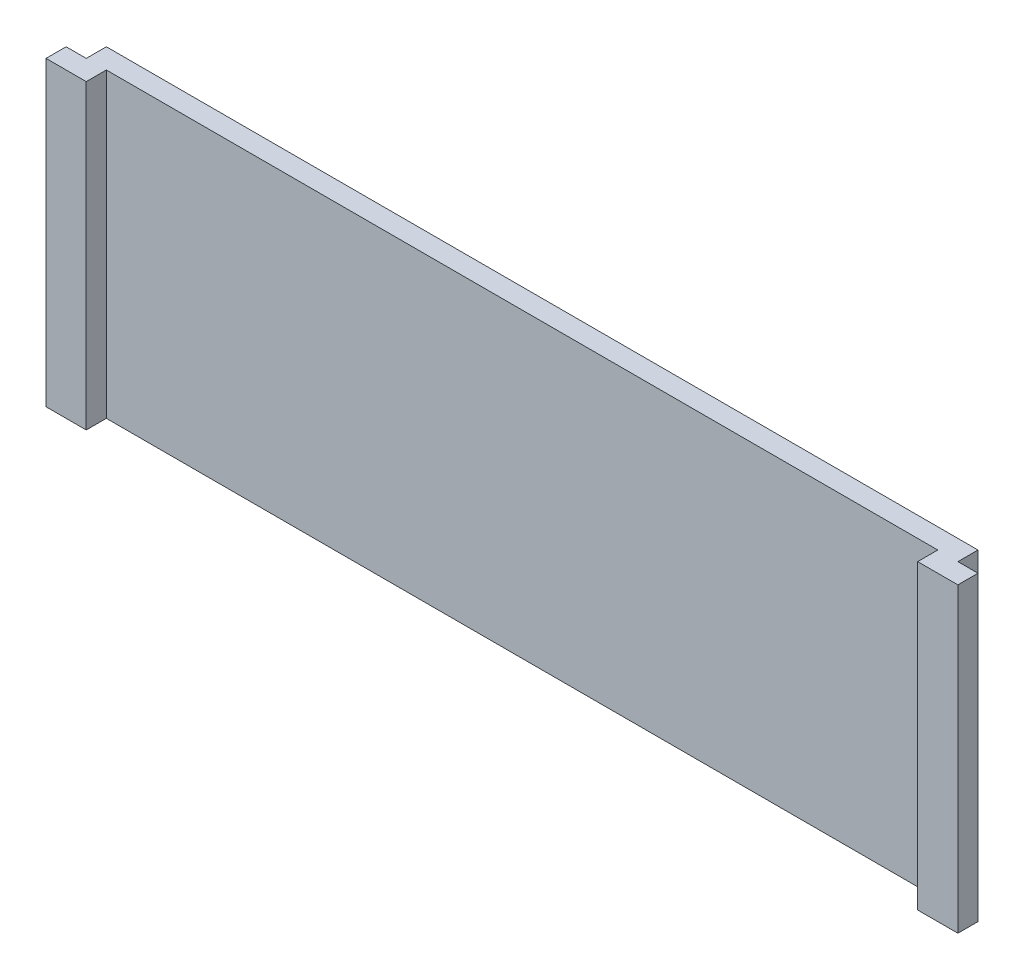
SolidWorks part; units mm, degrees
material "ABS"
ref_plane "前基準面" through (0, 0, 0) normal (0, 0, 1) x (1, 0, 0)
ref_plane "上基準面" through (0, 0, 0) normal (0, 1, 0) x (1, 0, 0)
ref_plane "右基準面" through (0, 0, 0) normal (1, 0, 0) x (0, 0, -1)
sketch "草圖1" plane through (0, 0, 0) normal (0, 0, 1) x (1, 0, 0)
  line L1 (-13.7647, 33.7349) -> (116.2353, 33.7349)
  line L2 (-13.7647, 33.7349) -> (-13.7647, -11.2651)
  line L3 (-13.7647, -11.2651) -> (116.2353, -11.2651)
  line L4 (116.2353, 33.7349) -> (116.2353, -11.2651)
  dimension "D1" = 130
  dimension "D2" = 45
extrude "填料-伸長1" add sketch "草圖1" along normal blind 3
sketch "草圖2" plane through (0, 0, 3) normal (0, 0, 1) x (1, 0, 0)
  line L0 (-13.7647, -11.2651) -> (116.2353, -11.2651) construction
  line L1 (-13.7647, 33.7349) -> (-10.7647, 33.7349)
  line L2 (-13.7647, 33.7349) -> (-13.7647, -11.2651)
  line L3 (-13.7647, -11.2651) -> (-10.7647, -11.2651)
  line L4 (-10.7647, 33.7349) -> (-10.7647, -11.2651)
  line L5 (-13.7647, -11.2651) -> (-13.7647, 33.7349)
  line L6 (116.2353, 33.7349) -> (113.2353, 33.7349)
  line L7 (116.2353, 33.7349) -> (116.2353, -11.2651)
  line L8 (116.2353, -11.2651) -> (113.2353, -11.2651)
  line L9 (113.2353, 33.7349) -> (113.2353, -11.2651)
  line L10 (-13.7647, -11.2651) -> (-16.7647, -11.2651)
  line L11 (-13.7647, 33.7349) -> (-16.7647, 33.7349)
  line L12 (-16.7647, -11.2651) -> (-16.7647, 33.7349)
  line L13 (116.2353, 33.7349) -> (116.2353, -11.2651)
  line L14 (116.2353, 33.7349) -> (119.2353, 33.7349)
  line L15 (116.2353, -11.2651) -> (119.2353, -11.2651)
  line L16 (119.2353, 33.7349) -> (119.2353, -11.2651)
  line M5 (-13.7647, 33.7349) -> (-13.7647, -11.2651)
  line M6 (-13.7647, -11.2651) -> (116.2353, -11.2651)
  line M7 (116.2353, -11.2651) -> (116.2353, 33.7349)
  line M8 (116.2353, 33.7349) -> (-13.7647, 33.7349)
  dimension "D1" = 3
  dimension "D2" = 3
  dimension "D3" = 3
  dimension "D4" = 3
extrude "填料-伸長2" add sketch "草圖2" along normal blind 3 contours L12 L10 L11 M5 | L4 M8 M5 M6 | L16 L14 L15 M7 | L9 M8 M6 M7
